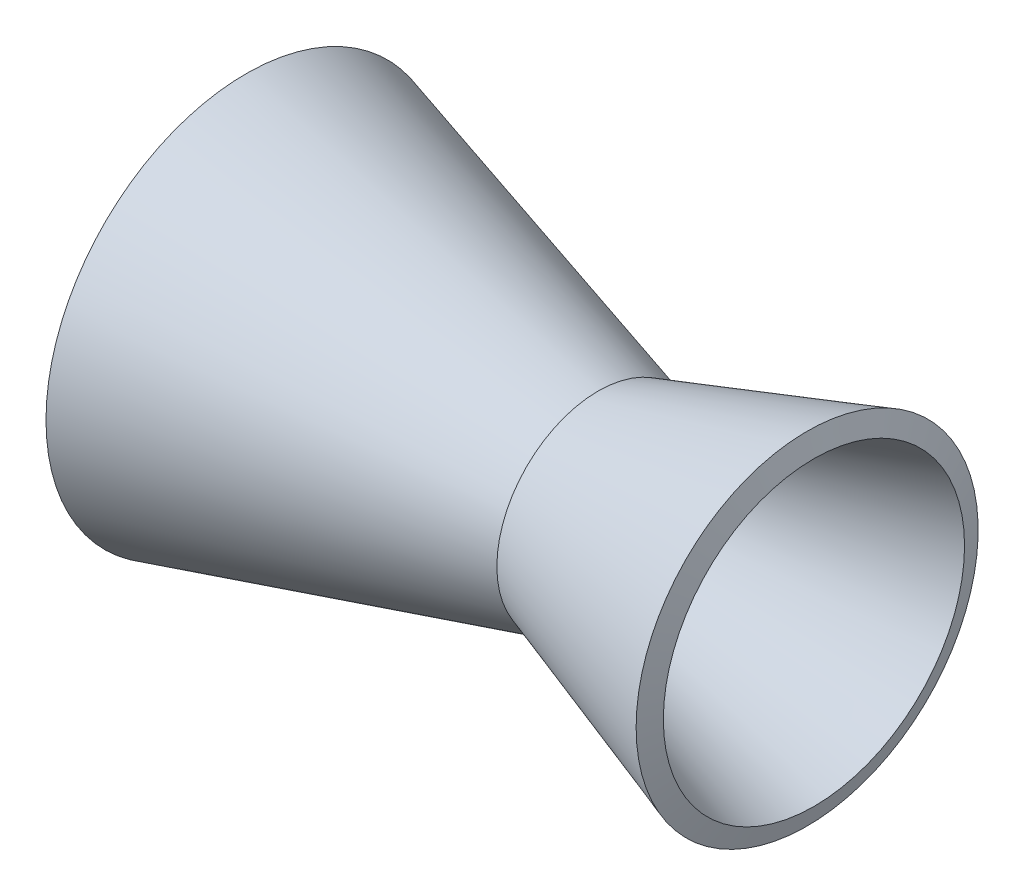
SolidWorks part; units mm, degrees
ref_plane "Front Plane" through (0, 0, 0) normal (0, 0, 1) x (1, 0, 0)
ref_plane "Top Plane" through (0, 0, 0) normal (0, 1, 0) x (1, 0, 0)
ref_plane "Right Plane" through (0, 0, 0) normal (1, 0, 0) x (0, 0, -1)
sketch "Sketch1" plane through (0, 0, 0) normal (0, 0, 1) x (1, 0, 0)
  line L5 (0, 0) -> (95.3663, 0) construction
  line L12 (70, 11) -> (100, 21)
  line L13 (20, 25) -> (70, 11)
  dimension "D2" = 11
revolve "Revolve-Thin1" add sketch "Sketch1" angle 360 about L5 wall 3
